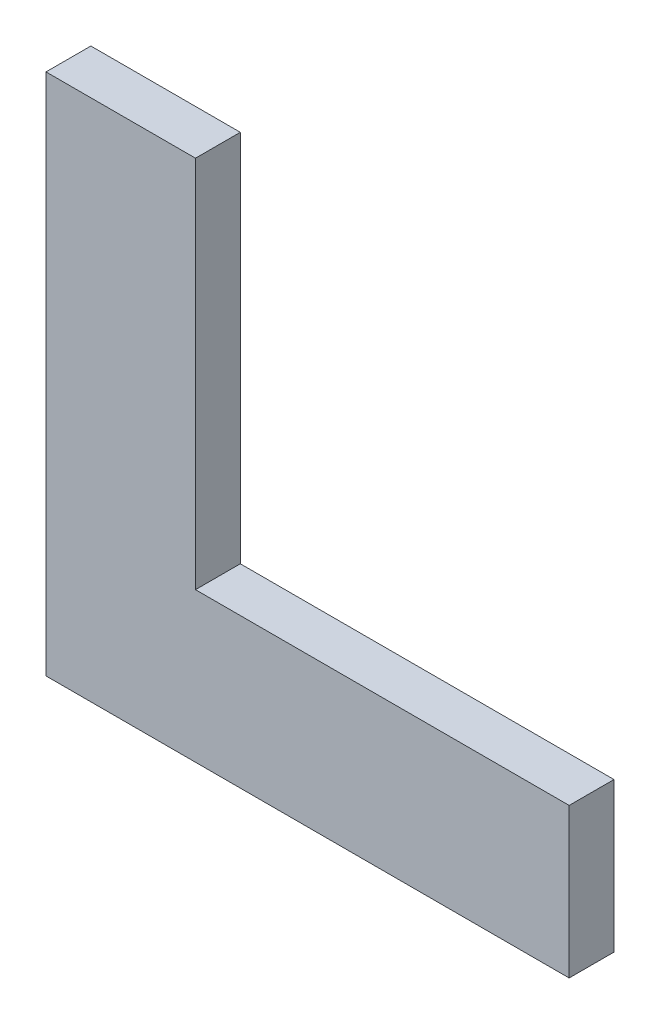
SolidWorks part; units mm, degrees
ref_plane "Front Plane" through (0, 0, 0) normal (0, 0, 1) x (1, 0, 0)
ref_plane "Top Plane" through (0, 0, 0) normal (0, 1, 0) x (1, 0, 0)
ref_plane "Right Plane" through (0, 0, 0) normal (1, 0, 0) x (0, 0, -1)
sketch "Sketch1" plane through (0, 0, 0) normal (0, 0, 1) x (1, 0, 0)
  line L1 (-57.0046, 25.4485) -> (-31.6046, 25.4485)
  line L2 (-57.0046, 25.4485) -> (-57.0046, -63.4515)
  line L3 (-57.0046, -63.4515) -> (-31.6046, -63.4515)
  line L4 (-31.6046, 25.4485) -> (-31.6046, -63.4515)
  line L5 (-57.0046, -38.0515) -> (31.8954, -38.0515)
  line L6 (-57.0046, -38.0515) -> (-57.0046, -63.4515)
  line L7 (-57.0046, -63.4515) -> (31.8954, -63.4515)
  line L8 (31.8954, -38.0515) -> (31.8954, -63.4515)
  dimension "D1" = 88.9
  dimension "D2" = 88.9
  dimension "D3" = 25.4
  dimension "D4" = 25.4
extrude "Boss-Extrude1" add sketch "Sketch1" along normal blind 7.62 contours L8 L5 L4 L7
